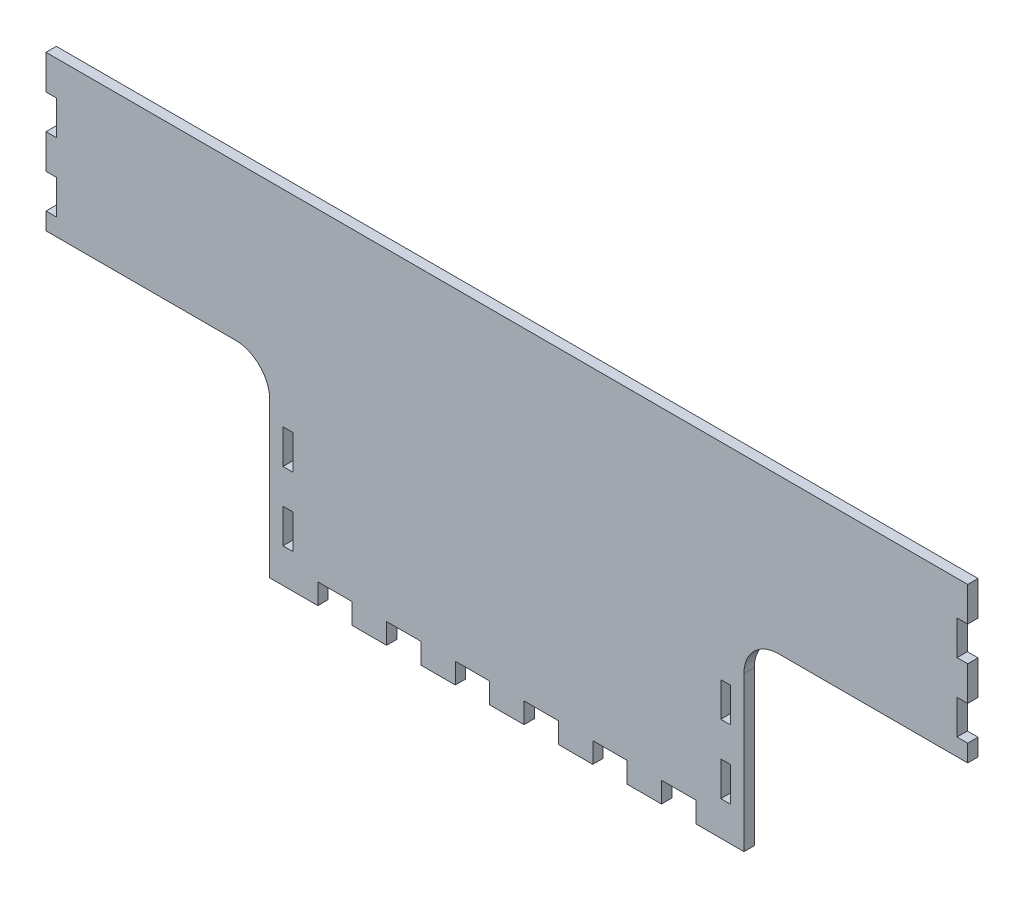
SolidWorks part; units mm, degrees
material "Pine"
ref_plane "Front Plane" through (0, 0, 0) normal (0, 0, 1) x (1, 0, 0)
ref_plane "Top Plane" through (0, 0, 0) normal (0, 1, 0) x (1, 0, 0)
ref_plane "Right Plane" through (0, 0, 0) normal (1, 0, 0) x (0, 0, -1)
sketch "Sketch1" plane through (0, 0, 0) normal (0, 0, 1) x (1, 0, 0)
  line L0 (-69, 54.9) -> (-69, 0)
  line L1 (-55, 0) -> (-65, 0) construction
  line L2 (-69, 6) -> (-69, 0) construction
  line L3 (-69, 0) -> (-55, 0)
  line L4 (-55, 0) -> (-55, 6)
  line L5 (-55, 0) -> (-55, 6) construction
  line L6 (-65, 6) -> (-55, 6) construction
  line L7 (-55, 6) -> (-45, 6)
  line L8 (-45, 6) -> (-45, 0)
  line L9 (-45, 0) -> (-35, 0)
  line L10 (-35, 0) -> (-35, 6)
  line L11 (-35, 6) -> (-25, 6)
  line L12 (-25, 6) -> (-25, 0)
  line L13 (-25, 0) -> (-15, 0)
  line L14 (-15, 0) -> (-15, 6)
  line L15 (-15, 6) -> (-5, 6)
  line L16 (-5, 6) -> (-5, 0)
  line L17 (-5, 0) -> (5, 0)
  line L19 (-134.1, 99.9) -> (-131.1, 99.9) construction
  line L20 (-131, 69.9) -> (-134.1, 69.9)
  line L21 (-134.1, 99.9) -> (134.1, 99.9)
  line L22 (0, 99.9) -> (0, 0) construction
  line L23 (131, 79.9) -> (131, 89.9)
  line L24 (-134.1, 69.9) -> (-134.1, 79.9)
  line L27 (-131, 59.9) -> (-134.1, 59.9)
  line L28 (-134.1, 54.9) -> (-134.1, 59.9)
  line L29 (-131, 79.9) -> (-134.1, 79.9)
  line L30 (-131, 89.9) -> (-134.1, 89.9)
  line L31 (-134.1, 89.9) -> (-134.1, 99.9)
  line L32 (-131, 59.9) -> (-131, 69.9)
  line L33 (131, 59.9) -> (131, 69.9)
  line L34 (-131, 99.9) -> (-134.1, 99.9) [skipped]
  line L35 (-131, 79.9) -> (-131, 89.9)
  line L36 (134.1, 89.9) -> (134.1, 99.9)
  line L37 (131, 89.9) -> (134.1, 89.9)
  line L38 (131, 79.9) -> (134.1, 79.9)
  line L39 (134.1, 54.9) -> (134.1, 59.9)
  line L40 (131, 59.9) -> (134.1, 59.9)
  line L41 (134.1, 69.9) -> (134.1, 79.9)
  line L42 (131, 69.9) -> (134.1, 69.9)
  line L43 (134.1, 54.9) -> (69, 54.9)
  line L44 (5, 6) -> (5, 0)
  line L45 (15, 6) -> (5, 6)
  line L46 (15, 0) -> (15, 6)
  line L47 (25, 0) -> (15, 0)
  line L48 (25, 6) -> (25, 0)
  line L49 (35, 6) -> (25, 6)
  line L50 (35, 0) -> (35, 6)
  line L51 (45, 0) -> (35, 0)
  line L52 (45, 6) -> (45, 0)
  line L53 (55, 6) -> (45, 6)
  line L54 (55, 0) -> (55, 6)
  line L55 (69, 0) -> (55, 0)
  line L56 (69, 54.9) -> (69, 0)
  line L57 (-69, 54.9) -> (-69, 0)
  line L58 (-69, 0) -> (-55, 0)
  line L59 (-55, 0) -> (-55, 6)
  line L60 (-55, 6) -> (-45, 6)
  line L61 (-45, 6) -> (-45, 0)
  line L62 (-45, 0) -> (-35, 0)
  line L63 (-35, 0) -> (-35, 6)
  line L64 (-35, 6) -> (-25, 6)
  line L65 (-25, 6) -> (-25, 0)
  line L66 (-25, 0) -> (-15, 0)
  line L67 (-15, 0) -> (-15, 6)
  line L68 (-15, 6) -> (-5, 6)
  line L69 (-5, 6) -> (-5, 0)
  line L70 (-134.1, 54.9) -> (-134.1, 99.9) construction
  line L71 (-131, 69.9) -> (-134.1, 69.9)
  line L72 (-134.1, 69.9) -> (-134.1, 79.9)
  line L73 (-131, 59.9) -> (-134.1, 59.9)
  line L74 (-134.1, 54.9) -> (-134.1, 59.9)
  line L75 (-131, 79.9) -> (-134.1, 79.9)
  line L76 (-131, 89.9) -> (-134.1, 89.9)
  line L77 (-134.1, 89.9) -> (-134.1, 99.9)
  line L78 (131, 79.9) -> (131, 89.9)
  line L79 (-131, 59.9) -> (-131, 69.9)
  line L80 (131, 59.9) -> (131, 69.9)
  line L81 (134.1, 89.9) -> (134.1, 99.9)
  line L82 (131, 89.9) -> (134.1, 89.9)
  line L83 (131, 79.9) -> (134.1, 79.9)
  line L84 (134.1, 54.9) -> (134.1, 59.9)
  line L85 (131, 59.9) -> (134.1, 59.9)
  line L86 (134.1, 69.9) -> (134.1, 79.9)
  line L87 (-131, 79.9) -> (-131, 89.9)
  line L88 (131, 69.9) -> (134.1, 69.9)
  line L89 (134.1, 54.9) -> (69, 54.9)
  line L90 (5, 6) -> (5, 0)
  line L91 (15, 6) -> (5, 6)
  line L92 (15, 0) -> (15, 6)
  line L93 (25, 0) -> (15, 0)
  line L94 (25, 6) -> (25, 0)
  line L95 (35, 6) -> (25, 6)
  line L96 (35, 0) -> (35, 6)
  line L97 (45, 0) -> (35, 0)
  line L98 (45, 6) -> (45, 0)
  line L99 (55, 6) -> (45, 6)
  line L100 (55, 0) -> (55, 6)
  line L101 (69, 0) -> (55, 0)
  line L102 (69, 54.9) -> (69, 0)
  line L106 (-134.1, 54.9) -> (-69, 54.9)
  dimension "D1" = 3.1
  dimension "D2" = 10
  dimension "D4" = 5
  dimension "D3" = 3
extrude "Boss-Extrude1" add sketch "Sketch1" along normal blind 3
fillet "Fillet1" radius 10 2 edges at (69, 54.9, 1.5) (-69, 54.9, 1.5)
sketch "Sketch2" plane through (0, 0, 0) normal (0, 0, -1) x (-1, 0, 0)
  line L1 (-65.1525, 10) -> (-62.2525, 10)
  line L2 (-65.1525, 10) -> (-65.1525, 20)
  line L3 (-65.1525, 20) -> (-62.2525, 20)
  line L4 (-62.2525, 10) -> (-62.2525, 20)
  line L5 (-69, 44.9) -> (-69, 0) construction
  line L6 (-69, 0) -> (-55, 0) construction
  line L7 (-65.1525, 30) -> (-62.2525, 30)
  line L8 (-65.1525, 30) -> (-65.1525, 40)
  line L9 (-65.1525, 40) -> (-62.2525, 40)
  line L10 (-62.2525, 30) -> (-62.2525, 40)
  line L11 (-65.1525, 10) -> (-65.1525, 30) construction
  line L12 (0, 0) -> (0, 99.9) construction
  line L13 (134.1, 99.9) -> (-134.1, 99.9) construction
  line L17 (65.1525, 10) -> (65.1525, 30) construction
  line L18 (62.2525, 30) -> (62.2525, 40)
  line L19 (65.1525, 40) -> (62.2525, 40)
  line L20 (65.1525, 30) -> (65.1525, 40)
  line L21 (65.1525, 30) -> (62.2525, 30)
  line L22 (62.2525, 10) -> (62.2525, 20)
  line L23 (65.1525, 20) -> (62.2525, 20)
  line L24 (65.1525, 10) -> (65.1525, 20)
  line L25 (65.1525, 10) -> (62.2525, 10)
  dimension "D1" = 10
  dimension "D2" = 2.9
  dimension "D3" = 3.8475
  dimension "D4" = 10
  dimension "D6" = 20
  dimension "D5" = 2
extrude "Cut-Extrude1" cut sketch "Sketch2" against normal through all
